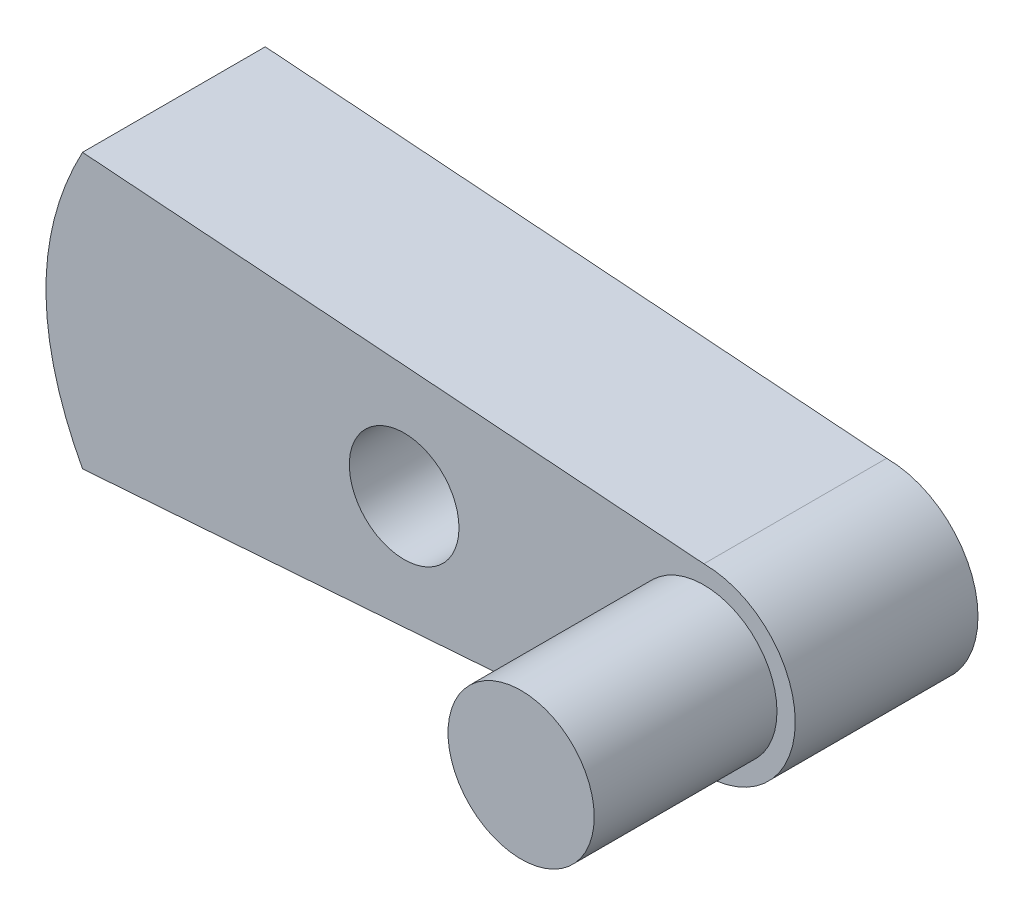
SolidWorks part; units mm, degrees
ref_plane "Front Plane" through (0, 0, 0) normal (0, 0, 1) x (1, 0, 0)
ref_plane "Top Plane" through (0, 0, 0) normal (0, 1, 0) x (1, 0, 0)
ref_plane "Right Plane" through (0, 0, 0) normal (1, 0, 0) x (0, 0, -1)
other "Center of Mass"
sketch "Sketch1" plane through (0, 0, 0) normal (0, 0, 1) x (1, 0, 0)
  line L4 (-5.4366, 31.2022) -> (37.7434, 28.0272)
  line L6 (37.7434, 15.3272) -> (-5.4366, 12.1522)
  arc A0 (37.7434, 28.0272) -> (37.7434, 15.3272) centre (37.7434, 21.6772) cw
  spline S0 degree 2 poles (-5.4366, 12.1522) (-10.5166, 21.6772) (-5.4366, 31.2022) knots 0 0 0 1 1 1
  dimension "D1" = 12.7
  dimension "D2" = 43.18
  dimension "D3" = 43.18
  dimension "D4" = 19.05
  dimension "D5" = 3.175
  dimension "D6" = 0
  dimension "D7" = 2.54
extrude "Boss-Extrude1" add sketch "Sketch1" along normal blind 12.7
sketch "Sketch2" plane through (0, 0, 0) normal (0, 0, 1) x (1, 0, 0)
  circle A0 centre (37.7434, 21.6772) radius 5.08
  dimension "D1" = 10.16
extrude "Boss-Extrude2" add sketch "Sketch2" along normal blind 25.4
sketch "Sketch3" plane through (0, 0, 12.7) normal (0, 0, 1) x (1, 0, 0)
  circle A0 centre (16.9154, 21.6772) radius 3.81
  dimension "D1" = 7.62
  dimension "D2" = 20.828
extrude "Cut-Extrude1" cut sketch "Sketch3" against normal blind 12.954 and the other way blind 6.858
